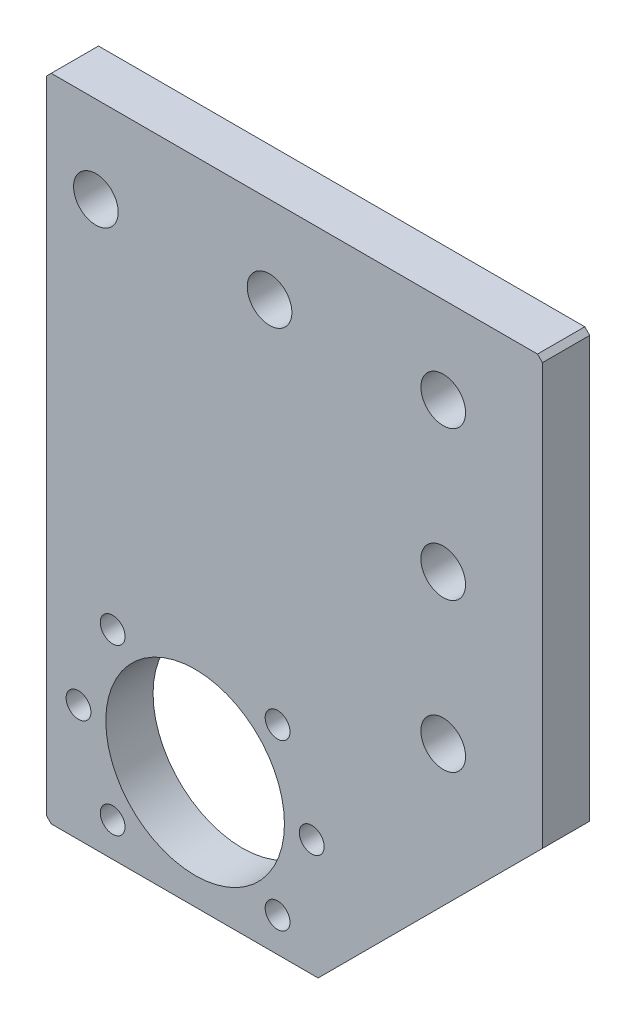
SolidWorks part; units mm, degrees
material "6061-T6 (SS)"
ref_plane "Front Plane" through (0, 0, 0) normal (0, 0, 1) x (1, 0, 0)
ref_plane "Top Plane" through (0, 0, 0) normal (0, 1, 0) x (1, 0, 0)
ref_plane "Right Plane" through (0, 0, 0) normal (1, 0, 0) x (0, 0, -1)
sketch "Sketch1" plane through (0, 0, 0) normal (0, 0, 1) x (1, 0, 0)
  line L0 (-20, 90) -> (15, 90) construction
  line L1 (-30, -23.5) -> (24.7843, -23.5)
  line L2 (-30, -23.5) -> (-30, 107.5)
  line L3 (-30, 107.5) -> (70, 107.5)
  line L4 (70, 21.7157) -> (70, 107.5)
  line L5 (15, 90) -> (50, 90) construction
  line L6 (50, 90) -> (50, 60) construction
  line L7 (50, 60) -> (50, 30) construction
  line L8 (0, -55) -> (0, 55) construction
  line L9 (0, 23.5) -> (-16.617, 16.617) construction
  line L10 (-16.617, 16.617) -> (-23.5, 0) construction
  line L11 (-23.5, 0) -> (-16.617, -16.617) construction
  line L12 (-16.617, -16.617) -> (0, -23.5) construction
  line L13 (0, -23.5) -> (16.617, -16.617) construction
  line L14 (16.617, -16.617) -> (23.5, 0) construction
  line L15 (23.5, 0) -> (16.617, 16.617) construction
  line L16 (16.617, 16.617) -> (0, 23.5) construction
  line L17 (24.7843, -23.5) -> (70, 21.7157)
  circle A0 centre (0, 0) radius 18
  circle A1 centre (0, 0) radius 21.7112 construction
  circle A2 centre (50, 30) radius 20 construction
  dimension "D1" = 36
  dimension "D2" = 30
  dimension "D3" = 23.5
  dimension "D4" = 17.5
  dimension "D5" = 70
  dimension "D6" = 30
  dimension "D7" = 10
  dimension "D8" = 20
  dimension "D9" = 90
  dimension "D10" = 47
  dimension "D11" = 35
  dimension "D12" = 45
extrude "Boss-Extrude1" add sketch "Sketch1" along normal mid plane 9.525
hole_wizard "M8 Clearance Hole1" positions "Sketch2" profile "Sketch3" hole size "M8" standard "ANSI Metric" end condition up to next
sketch "Sketch2" plane through (0, 0, 4.7625) normal (0, 0, 1) x (1, 0, 0)
  point P0 (-20, 90)
  point P3 (15, 90)
  point P6 (50, 90)
  point P9 (50, 60)
  point P12 (50, 30)
sketch "Sketch3" plane through (-20, 90, 4.7625) normal (1, 0, 0) x (0, -1, 0)
  line L0 (0, 0) -> (0, 9.525)
  line L1 (0, 9.525) -> (4.5, 9.525)
  line L2 (4.5, 9.525) -> (4.5, 0)
  line L5 (4.5, 0) -> (0, 0)
  line L11 (0, -6.35) -> (0, 107.95) construction
  dimension "Thru Hole Dia." = 9
  dimension "Thru Hole Depth" = 9.525
hole_wizard "M6x1.0 Tapped Hole1" positions "Sketch4" profile "Sketch5" tap size "M6x1.0" standard "ANSI Metric" end condition up to next
sketch "Sketch4" plane through (0, 0, 4.7625) normal (0, 0, 1) x (1, 0, 0)
  point P3 (16.617, 16.617)
  point P6 (23.5, 0)
  point P9 (16.617, -16.617)
  point P12 (-16.617, -16.617)
  point P15 (-23.5, 0)
  point P18 (-16.617, 16.617)
sketch "Sketch5" plane through (16.617, 16.617, 4.7625) normal (1, 0, 0) x (0, -1, 0)
  line L0 (0, 0) -> (0, 9.525)
  line L1 (0, 9.525) -> (2.5, 9.525)
  line L2 (2.5, 9.525) -> (2.5, 0)
  line L5 (2.5, 0) -> (0, 0)
  line L11 (0, -6.35) -> (0, 107.95) construction
  dimension "Thru Tap Drill Dia." = 5
  dimension "Thru Tap Drill Depth" = 9.525
cosmetic thread "Hole Thread1"
cosmetic thread "Hole Thread2"
cosmetic thread "Hole Thread3"
cosmetic thread "Hole Thread4"
cosmetic thread "Hole Thread5"
cosmetic thread "Hole Thread6"
chamfer "Chamfer1" distance 1 3 edges at (-30, -23.5, 0) (70, 107.5, 0) (-30, 107.5, 0)
